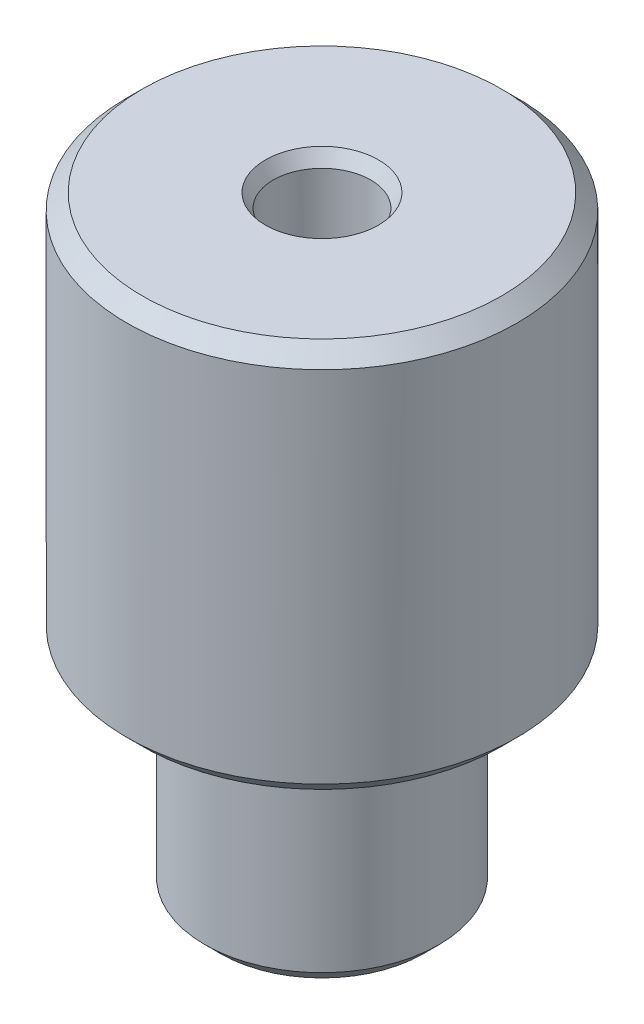
SolidWorks part; units mm, degrees
material "Plain Carbon Steel"
ref_plane "Front Plane" through (0, 0, 0) normal (0, 0, 1) x (1, 0, 0)
ref_plane "Top Plane" through (0, 0, 0) normal (0, 1, 0) x (1, 0, 0)
ref_plane "Right Plane" through (0, 0, 0) normal (1, 0, 0) x (0, 0, -1)
sketch "Sketch1" plane through (0, 0, 0) normal (0, 0, 1) x (1, 0, 0)
  line L0 (0, 0) -> (25, 0)
  line L1 (25, 0) -> (25, -50)
  line L2 (25, -50) -> (15, -50)
  line L3 (15, -50) -> (15, -78)
  line L4 (15, -78) -> (0, -78)
  line L5 (0, -78) -> (0, 0)
  line L6 (0, 5) -> (0, -83) construction
  dimension "D1" = 5
  dimension "D2" = 5
  dimension "D3" = 30
  dimension "D4" = 50
  dimension "D5" = 50
  dimension "D6" = 28
revolve "Revolve1" add sketch "Sketch1" angle 360 about L6
chamfer "Chamfer1" distance 2 angle 45 3 edges at (-15, -78, 0) (-25, -50, 0) (-25, 0, 0)
cosmetic thread "Cosmetic Thread1"
hole_wizard "Ø12.5 (12.5) Diameter Hole1" positions "Sketch4" profile "Sketch3" hole size "Ø12.5" standard "ISO" end condition through all
sketch "Sketch4" plane through (0, 0, 0) normal (0, 1, 0) x (1, 0, 0)
  point P0 (0, 0)
sketch "Sketch3" plane through (0, 0, 0) normal (1, 0, 0) x (0, 0, 1)
  line L0 (0, 0) -> (0, 78)
  line L1 (0, 78) -> (6.25, 78)
  line L2 (6.25, 78) -> (6.25, 0)
  line L5 (6.25, 0) -> (0, 0)
  line L11 (0, -6.35) -> (0, 107.95) construction
  dimension "Thru Hole Dia." = 12.5
  dimension "Thru Hole Depth" = 78
chamfer "Chamfer2" distance 1 angle 60 2 edges at (0, -78, 6.25) (0, 0, 6.25)
